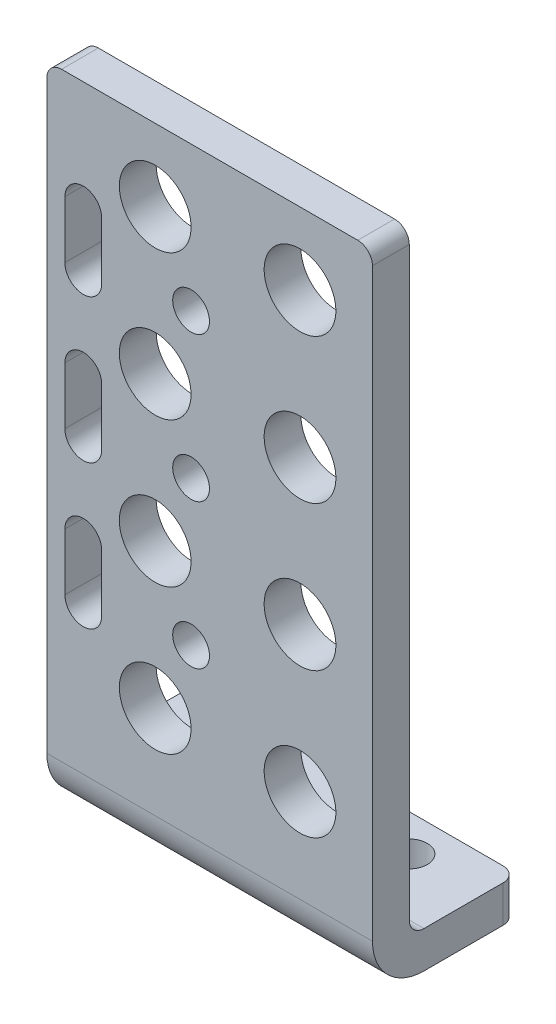
SolidWorks part; units mm, degrees
ref_plane "Front Plane" through (0, 0, 0) normal (0, 0, 1) x (1, 0, 0)
ref_plane "Top Plane" through (0, 0, 0) normal (0, 1, 0) x (1, 0, 0)
ref_plane "Right Plane" through (0, 0, 0) normal (1, 0, 0) x (0, 0, -1)
sketch "Sketch6" plane through (0, 0, 0) normal (1, 0, 0) x (0, 0, -1)
  line L4 (0, 7.112) -> (0, 89.916)
  line L5 (0, 89.916) -> (5.08, 89.916)
  line L6 (7.112, 0) -> (20.066, 0)
  line L7 (20.066, 0) -> (20.066, 5.08)
  line L8 (20.066, 5.08) -> (7.112, 5.08)
  line L9 (5.08, 7.112) -> (5.08, 89.916)
  arc A0 (5.08, 7.112) -> (7.112, 5.08) centre (7.112, 7.112) ccw
  arc A1 (0, 7.112) -> (7.112, 0) centre (7.112, 7.112) ccw
  point P12 (0, 0)
  dimension "D2" = 2.032
  dimension "D3" = 7.112
  dimension "D1" = 89.916
  dimension "D4" = 20.066
extrude "Boss-Extrude6" add sketch "Sketch6" along normal blind 44.958
sketch "Sketch12" plane through (0, 0, -5.08) normal (0, 0, -1) x (-1, 0, 0)
  line L0 (-44.958, 0) -> (-34.9504, 0) construction
  line L1 (-44.958, 0) -> (0, 0) construction
  line L2 (-34.9504, 0) -> (-34.9504, 89.916) construction
  line L3 (-44.958, 89.916) -> (0, 89.916) construction
  line L4 (-34.9504, 0) -> (-14.9606, 0) construction
  line L5 (-14.9606, 0) -> (-14.9606, 89.916) construction
  line L6 (-14.9606, 0) -> (-14.9606, 19.9898) construction
  line L7 (-14.9606, 19.9898) -> (0, 19.9898) construction
  line L8 (0, 11.0363) -> (0, -11.0363) construction
  line L9 (-14.9606, 19.9898) -> (-44.958, 19.9898) construction
  line L10 (-44.958, 7.112) -> (-44.958, 89.916) construction
  line L11 (-44.958, 19.9898) -> (-14.9606, 19.9898) construction
  line L12 (-14.9606, 19.9898) -> (-14.9606, 29.9847) construction
  line L13 (-14.9606, 29.9847) -> (-34.9504, 29.9847) construction
  line L14 (-34.9504, 29.9847) -> (-34.9504, 49.9745) construction
  line L15 (-34.9504, 49.9745) -> (-14.9606, 49.9745) construction
  line L16 (-14.9606, 49.9745) -> (-14.9606, 79.9592) construction
  line L17 (-14.9606, 79.9592) -> (-34.9504, 79.9592) construction
  line L18 (-14.9606, 19.9898) -> (-14.9606, 39.9796) construction
  line L19 (-14.9606, 19.9898) -> (-14.9606, 29.9847) construction
  line L20 (-14.9606, 29.9847) -> (-34.9504, 29.9847) construction
  line L21 (-19.9136, 79.9592) -> (-19.9136, 19.9898) construction
  line L22 (-14.9606, 39.9796) -> (-14.9606, 49.9745) construction
  line L23 (-14.9606, 49.9745) -> (-34.9504, 49.9745) construction
  line L24 (-34.9504, 49.9745) -> (-14.9606, 49.9745) construction
  line L25 (0, 89.916) -> (-2.4892, 89.916) construction
  line L26 (-2.4892, 89.916) -> (-2.4892, 0) construction
  line L27 (-2.4892, 0) -> (-2.4892, 89.916) construction
  line L28 (-2.4892, 89.916) -> (-2.4892, 74.9046) construction
  line L29 (-2.4892, 74.9046) -> (0, 74.9046) construction
  line L30 (0, 74.9046) -> (-2.4892, 74.9046) construction
  line L31 (-2.4892, 74.9046) -> (-2.4892, 67.0306) construction
  line L32 (-2.4892, 67.0306) -> (-14.9606, 67.0306) construction
  line L33 (-14.9606, 67.0306) -> (-2.4892, 67.0306) construction
  line L34 (-2.4892, 67.0306) -> (-2.4892, 55.0418) construction
  line L35 (-2.4892, 55.0418) -> (-8.7249, 55.0418) construction
  line L36 (-8.7249, 55.0418) -> (-2.4892, 55.0418) construction
  line L37 (-2.4892, 55.0418) -> (-2.4892, 47.1678) construction
  line L38 (-2.4892, 47.1678) -> (-8.7249, 47.1678) construction
  line L39 (-19.9136, 69.9643) -> (0, 69.9643) construction
  line L40 (-2.4892, 74.9046) -> (-9.5743, 74.9046) construction
  line L41 (-2.4892, 67.0306) -> (-9.5743, 67.0306) construction
  line L42 (-9.5743, 67.0306) -> (-9.5743, 74.9046) construction
  line L43 (-9.5743, 74.9046) -> (-2.4892, 74.9046) construction
  line L44 (-2.4892, 74.9046) -> (-5.0292, 74.9046) construction
  line L45 (-5.0292, 74.9046) -> (-5.0292, 89.916) construction
  line L46 (-5.0292, 89.916) -> (-5.0292, 56.2523) construction
  line L47 (-5.0292, 74.9046) -> (-5.0292, 67.0306) construction
  line L48 (-2.4892, 74.9046) -> (-2.4892, 67.0306)
  line L49 (-7.5692, 74.9046) -> (-7.5692, 67.0306)
  line L50 (-5.0292, 55.0418) -> (-5.0292, 47.1678) construction
  line L51 (-2.4892, 55.0418) -> (-2.4892, 47.1678)
  line L52 (-7.5692, 55.0418) -> (-7.5692, 47.1678)
  line L53 (-5.0292, 35.179) -> (-5.0292, 27.305) construction
  line L54 (-2.4892, 35.179) -> (-2.4892, 27.305)
  line L55 (-7.5692, 35.179) -> (-7.5692, 27.305)
  circle A0 centre (-34.9504, 79.9592) radius 4.953
  circle A1 centre (-14.9606, 79.9592) radius 4.953
  circle A2 centre (-14.9606, 59.9694) radius 4.953
  circle A3 centre (-14.9606, 39.9796) radius 4.953
  circle A4 centre (-14.9606, 19.9898) radius 4.953
  circle A5 centre (-34.9504, 59.9694) radius 4.953
  circle A6 centre (-34.9504, 39.9796) radius 4.953
  circle A7 centre (-34.9504, 19.9898) radius 4.953
  circle A8 centre (-19.9136, 49.9745) radius 2.54
  circle A9 centre (-19.9136, 69.9643) radius 2.54
  circle A10 centre (-19.9136, 29.9847) radius 2.54
  arc A11 (-2.4892, 74.9046) -> (-7.5692, 74.9046) centre (-5.0292, 74.9046) ccw
  arc A12 (-7.5692, 67.0306) -> (-2.4892, 67.0306) centre (-5.0292, 67.0306) ccw
  arc A13 (-2.4892, 55.0418) -> (-7.5692, 55.0418) centre (-5.0292, 55.0418) ccw
  arc A14 (-7.5692, 47.1678) -> (-2.4892, 47.1678) centre (-5.0292, 47.1678) ccw
  arc A15 (-2.4892, 35.179) -> (-7.5692, 35.179) centre (-5.0292, 35.179) ccw
  arc A16 (-7.5692, 27.305) -> (-2.4892, 27.305) centre (-5.0292, 27.305) ccw
  point P58 (-5.0292, 70.9676)
  point P72 (-5.0292, 51.1048)
  point P79 (-5.0292, 31.242)
  dimension "D1" = 2
  dimension "D3" = 2
  dimension "D5" = 3
  dimension "D2" = 4
  dimension "D4" = 2
extrude "Cut-Extrude1" cut sketch "Sketch12" against normal through all
fillet "Fillet4" radius 2.032 1 edges at (44.958, 89.916, -2.54)
fillet "Fillet5" radius 2.032 1 edges at (44.958, 2.54, -20.066)
fillet "Fillet6" radius 2.032 1 edges at (0, 2.54, -20.066)
fillet "Fillet7" radius 2.032 1 edges at (0, 89.916, -2.54)
sketch "Sketch15" plane through (0, 5.08, 0) normal (0, 1, 0) x (1, 0, 0)
  line L0 (0, 14.986) -> (15.0114, 14.986) construction
  line L1 (0, 18.034) -> (0, 7.112) construction
  line L2 (15.0114, 14.986) -> (15.0114, 8.716) construction
  line L3 (15.0114, 8.716) -> (15.0114, 11.851) construction
  line L4 (15.0114, 11.851) -> (0, 11.851) construction
  line L5 (0, 11.851) -> (0, 14.986) construction
  line L6 (0, 14.986) -> (0, 0) construction
  line L7 (0, 14.986) -> (44.958, 14.986) construction
  line L8 (44.958, 18.034) -> (44.958, 7.112) construction
  line L9 (44.958, 14.986) -> (15.0114, 14.986) construction
  line L10 (15.0114, 14.986) -> (0, 14.986) construction
  line L11 (15.0114, 14.986) -> (35.0012, 14.986) construction
  circle A0 centre (15.0114, 14.986) radius 2.54
  circle A1 centre (35.0012, 14.986) radius 2.54
extrude "Cut-Extrude2" cut sketch "Sketch15" against normal through all
